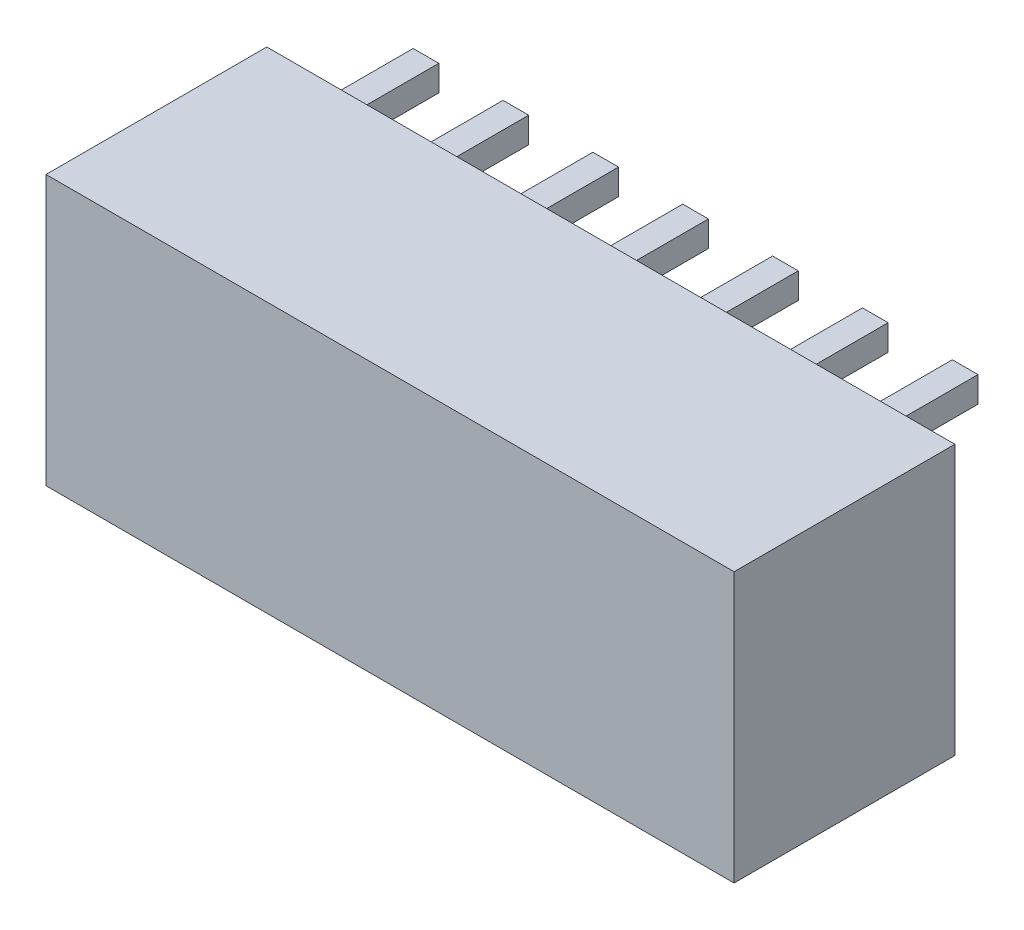
SolidWorks part; units mm, degrees
ref_plane "Спереди" through (0, 0, 0) normal (0, 0, 1) x (1, 0, 0)
ref_plane "Сверху" through (0, 0, 0) normal (0, 1, 0) x (1, 0, 0)
ref_plane "Справа" through (0, 0, 0) normal (1, 0, 0) x (0, 0, -1)
sketch "Эскиз1" plane through (0, 0, 0) normal (0, 0, 1) x (1, 0, 0)
  line L1 (-13.4, 0) -> (13.4, 0)
  line L2 (-13.4, 0) -> (-13.4, 10.5)
  line L3 (-13.4, 10.5) -> (13.4, 10.5)
  line L4 (13.4, 0) -> (13.4, 10.5)
  point P0 (0, 0)
  dimension "D1" = 26.8
  dimension "D2" = 10.5
extrude "Бобышка-Вытянуть1" add sketch "Эскиз1" along normal blind 8.6
sketch "Эскиз2" plane through (0, 0, 0) normal (0, -1, 0) x (1, 0, 0)
  line L0 (-12.4, 6.6) -> (12.4, 6.6)
  line L1 (12.4, 6.6) -> (12.4, 0.2)
  line L2 (12.4, 0.2) -> (10.2, 0.2)
  line L3 (10.2, 0.2) -> (10.2, 1.8)
  line L4 (10.2, 1.8) -> (-8.6, 1.8)
  line L5 (-8.6, 1.8) -> (-8.6, 0.2)
  line L6 (-8.6, 0.2) -> (-10.8, 0.2)
  line L7 (-12.4, 6.6) -> (-12.4, 1.8)
  line L8 (-12.4, 1.8) -> (-10.8, 1.8)
  line L9 (-10.8, 1.8) -> (-10.8, 0.2)
  line L10 (13.4, 8.6) -> (13.4, 0) construction
  line L11 (-13.4, 8.6) -> (-13.4, 0) construction
  line L12 (-13.4, 8.6) -> (13.4, 8.6) construction
  dimension "D1" = 4.8
  dimension "D2" = 6.4
  dimension "D3" = 2.2
  dimension "D4" = 2.2
  dimension "D5" = 3.2
  dimension "D6" = 4.8
  dimension "D7" = 1
  dimension "D8" = 2
extrude "Вырез-Вытянуть1" cut sketch "Эскиз2" against normal blind 7
sketch "Эскиз3" plane through (0, 0, 0) normal (0, 0, -1) x (-1, 0, 0)
  line L0 (13.4, 0) -> (-13.4, 0) construction
  line L1 (11, 10) -> (10, 10)
  line L2 (11, 10) -> (11, 9)
  line L3 (11, 9) -> (10, 9)
  line L4 (10, 10) -> (10, 9)
  line L5 (11, 10) -> (10, 9) construction
  line L6 (11, 9) -> (10, 10) construction
  line L7 (13.4, 10.5) -> (13.4, 0) construction
  point P0 (10.5, 9.5)
  dimension "D1" = 1
  dimension "D2" = 9.5
  dimension "D3" = 2.9
extrude "Бобышка-Вытянуть2" add sketch "Эскиз3" along normal blind 3.6 and the other way blind 5
chamfer "Фаска1" distance 0.3 distance2 0.3 4 edges at (-10, 9.5, -3.6) (-10.5, 9, -3.6) (-11, 9.5, -3.6) (-10.5, 10, -3.6)
sketch "Эскиз4" plane through (0, 7, 0) normal (0, -1, 0) x (1, 0, 0)
  line L0 (-11, 0) -> (-11, -3.3) construction
  line L1 (-11, 3.85) -> (-10, 3.85)
  line L2 (-11, 3.85) -> (-11, 4.85)
  line L3 (-11, 4.85) -> (-10, 4.85)
  line L4 (-10, 3.85) -> (-10, 4.85)
  line L5 (-10, 0) -> (-10, -3.3) construction
  line L7 (-13.4, 0) -> (13.4, 0) construction
  dimension "D1" = 3.85
extrude "Бобышка-Вытянуть3" add sketch "Эскиз4" along normal blind 5
pattern_linear "Линейный массив1" count 7 spacing 3.5 along (1, 0, 0) of "Бобышка-Вытянуть2", "Фаска1", "Бобышка-Вытянуть3"
equation "\"N\"= 7"
equation "\"D1@Эскиз1\"= ( \"N\" - 1 ) * 3.5 + 5.8"
equation "\"D1@Линейный массив1\"=\"N\""
